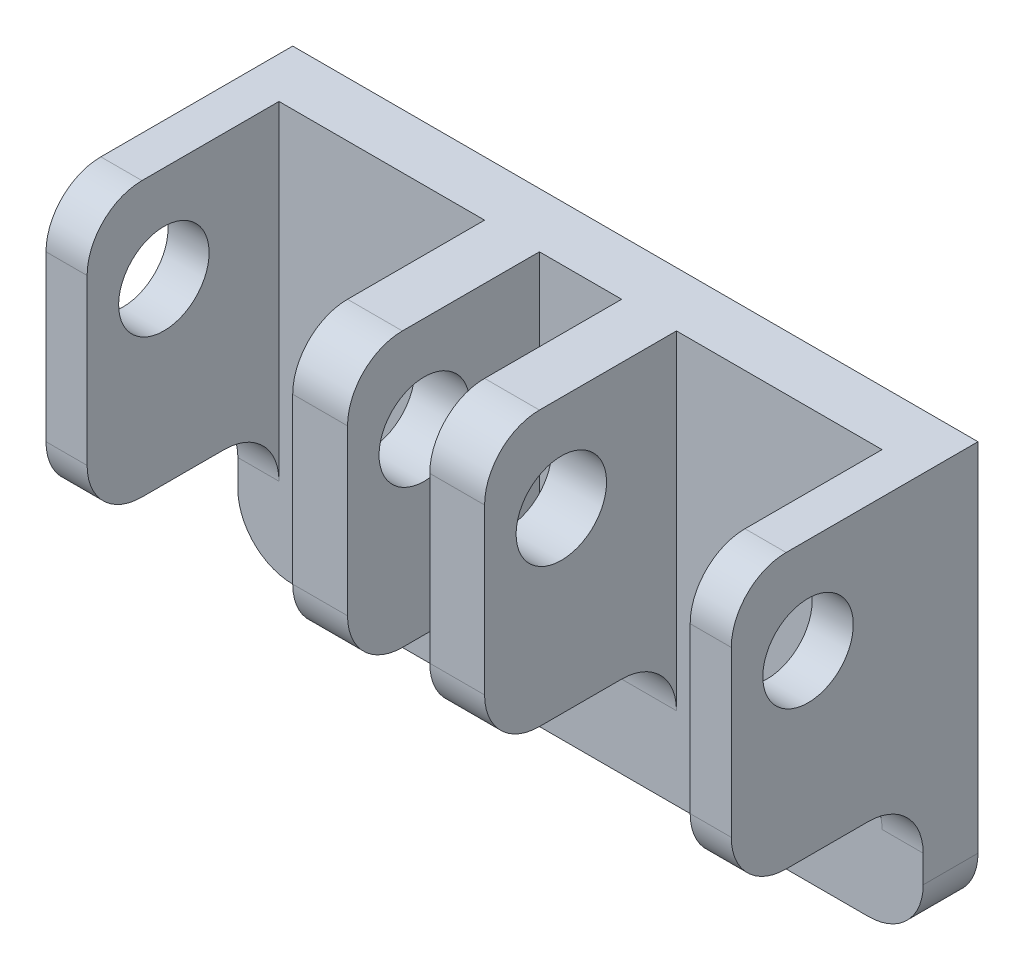
SolidWorks part; units mm, degrees
ref_plane "前视基准面" through (0, 0, 0) normal (0, 0, 1) x (1, 0, 0)
ref_plane "上视基准面" through (0, 0, 0) normal (0, 1, 0) x (1, 0, 0)
ref_plane "右视基准面" through (0, 0, 0) normal (1, 0, 0) x (0, 0, -1)
sketch "草图2" plane through (0, 0, 0) normal (0, 0, 1) x (1, 0, 0)
  line L0 (-8, -3.5) -> (8, -3.5) construction
  line L1 (-12.5, 7.5) -> (12.5, 7.5)
  line L2 (-12.5, 7.5) -> (-12.5, -7.5)
  line L3 (-12.5, -7.5) -> (12.5, -7.5)
  line L4 (12.5, 7.5) -> (12.5, -7.5)
  line L5 (-12.5, 7.5) -> (12.5, -7.5) construction
  line L6 (-12.5, -7.5) -> (12.5, 7.5) construction
  circle A0 centre (-8, -3.5) radius 1.6
  circle A2 centre (8, -3.5) radius 1.6
  point P4 (0, 0)
  point P5 (0, -3.5)
  dimension "D3" = 3.2
  dimension "D4" = 3.2
  dimension "D1" = 25
  dimension "D2" = 15
  dimension "D5" = 4
  dimension "D6" = 16
extrude "凸台-拉伸1" add sketch "草图2" along normal blind 2
sketch "草图3" plane through (0, 0, 2) normal (0, 0, 1) x (1, 0, 0)
  line L0 (12.5, 7.5) -> (-12.5, 7.5) construction
  line L1 (-12.5, 7.5) -> (-11, 7.5)
  line L2 (-12.5, 7.5) -> (-12.5, -2.5)
  line L3 (-12.5, -2.5) -> (-11, -2.5)
  line L4 (-11, 7.5) -> (-11, -2.5)
  line L5 (-3.5, 7.5) -> (-1.5, 7.5)
  line L6 (-3.5, 7.5) -> (-3.5, -2.5)
  line L7 (-3.5, -2.5) -> (-1.5, -2.5)
  line L8 (-1.5, 7.5) -> (-1.5, -2.5)
  line L9 (-12.5, -7.5) -> (12.5, -7.5) construction
  line L10 (1.5, 7.5) -> (3.5, 7.5)
  line L11 (1.5, 7.5) -> (1.5, -2.5)
  line L12 (1.5, -2.5) -> (3.5, -2.5)
  line L13 (3.5, 7.5) -> (3.5, -2.5)
  line L14 (12.5, 7.5) -> (11, 7.5)
  line L15 (12.5, 7.5) -> (12.5, -2.5)
  line L16 (12.5, -2.5) -> (11, -2.5)
  line L17 (11, 7.5) -> (11, -2.5)
  dimension "D1" = 1.5
  dimension "D2" = 2
  dimension "D3" = 2
  dimension "D4" = 1.5
  dimension "D5" = 7.5
  dimension "D6" = 7.5
  dimension "D7" = 5
extrude "凸台-拉伸2" add sketch "草图3" along normal blind 7
fillet "圆角1" radius 2 14 edges at (-11.75, 7.5, 9) (-2.5, 7.5, 9) (2.5, 7.5, 9) (11.75, 7.5, 9) (11.75, -2.5, 9) (-11.75, -2.5, 9) (-2.5, -2.5, 9) (2.5, -2.5, 9) (11.75, -2.5, 2) (2.5, -2.5, 2) (-2.5, -2.5, 2) (-11.75, -2.5, 2) (12.5, -7.5, 1) (-12.5, -7.5, 1)
sketch "草图4" plane through (-12.5, 0, 0) normal (-1, 0, 0) x (0, 0, 1)
  line L1 (7, 7.5) -> (0, 7.5) construction
  line L2 (0, 7.5) -> (0, -5.5) construction
  circle A0 centre (6.2, 4) radius 1.65
  point P6 (5.9184, 5.31)
  dimension "D1" = 3.3
  dimension "D3" = 3.5
  dimension "6" = 6.2
extrude "切除-拉伸1" cut sketch "草图4" against normal through all
